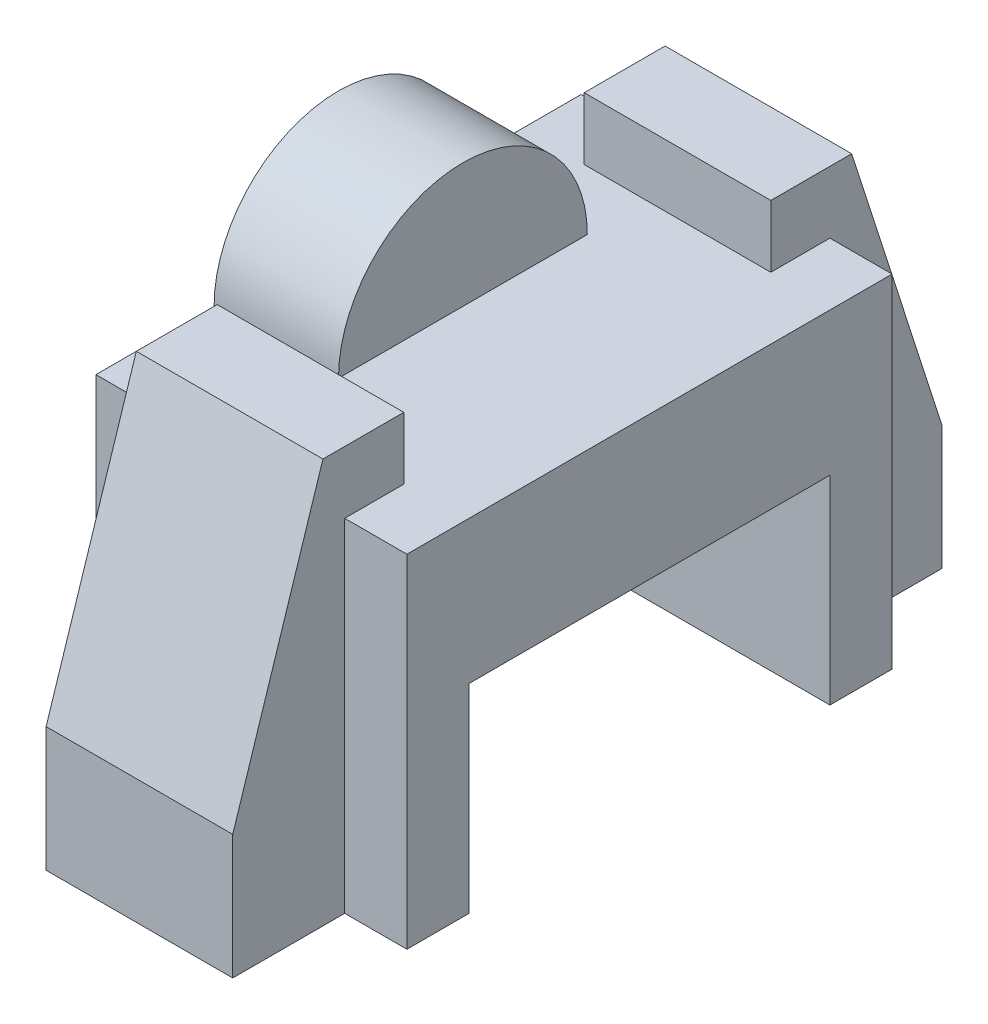
SolidWorks part; units mm, degrees
ref_plane "Alzado" through (0, 0, 0) normal (0, 0, 1) x (1, 0, 0)
ref_plane "Planta" through (0, 0, 0) normal (0, 1, 0) x (1, 0, 0)
ref_plane "Vista lateral" through (0, 0, 0) normal (1, 0, 0) x (0, 0, -1)
sketch "Croquis1" plane through (0, 0, 0) normal (1, 0, 0) x (0, 0, -1)
  line L0 (29, -27.5) -> (39, -27.5)
  line L1 (-39, 27.5) -> (39, 27.5)
  line L2 (-39, 27.5) -> (-39, -27.5)
  line L3 (-39, -27.5) -> (-29, -27.5)
  line L4 (39, 27.5) -> (39, -27.5)
  line L5 (-39, 27.5) -> (39, -27.5) construction
  line L6 (-39, -27.5) -> (39, 27.5) construction
  line L8 (-29, -27.5) -> (-29, 4.5)
  line L9 (-29, 4.5) -> (29, 4.5)
  line L10 (29, -27.5) -> (29, 4.5)
  point P0 (0, 0)
  point P10 (0, 4.5)
  dimension "D1" = 58
  dimension "D2" = 78
  dimension "D3" = 32
  dimension "D4" = 55
extrude "Saliente-Extruir2" add sketch "Croquis1" along normal mid plane 50
sketch "Croquis3" plane through (0, 0, 0) normal (1, 0, 0) x (0, 0, -1)
  line L0 (0, 0) -> (0, 29.0772) construction
  line L1 (-39, 27.5) -> (-29.5, 27.5)
  line L2 (39, 27.5) -> (-39, 27.5) construction
  line L3 (-29.5, 27.5) -> (-29.5, 37.5)
  line L4 (-29.5, 37.5) -> (-42.5, 37.5)
  line L5 (-42.5, 37.5) -> (-57, -7.5)
  line L6 (-57, -7.5) -> (-57, -27.5)
  line L7 (-57, -27.5) -> (-39, -27.5)
  line L8 (-39, -27.5) -> (-39, 27.5)
  line L9 (42.5, 37.5) -> (57, -7.5)
  line L10 (57, -7.5) -> (57, -27.5)
  line L11 (57, -27.5) -> (39, -27.5)
  line L12 (39, -27.5) -> (39, 27.5)
  line L13 (39, 27.5) -> (29.5, 27.5)
  line L14 (29.5, 37.5) -> (42.5, 37.5)
  line L15 (29.5, 27.5) -> (29.5, 37.5)
  dimension "D1" = 18
  dimension "D2" = 65
  dimension "D3" = 20
  dimension "D4" = 13
  dimension "D5" = 85
extrude "Saliente-Extruir3" add sketch "Croquis3" along normal mid plane 30
sketch "Croquis4" plane through (25, 0, 0) normal (1, 0, 0) x (0, 0, -1)
  line L0 (39, 27.5) -> (-39, 27.5) construction
  line L1 (-20, 27.5) -> (20, 27.5)
  arc A0 (20, 27.5) -> (-20, 27.5) centre (0, 27.5) ccw
  dimension "D1" = 20
extrude "Saliente-Extruir4" add sketch "Croquis4" along normal blind 20 from surface at -50 starting at face at (-25, -5.75, 0)
